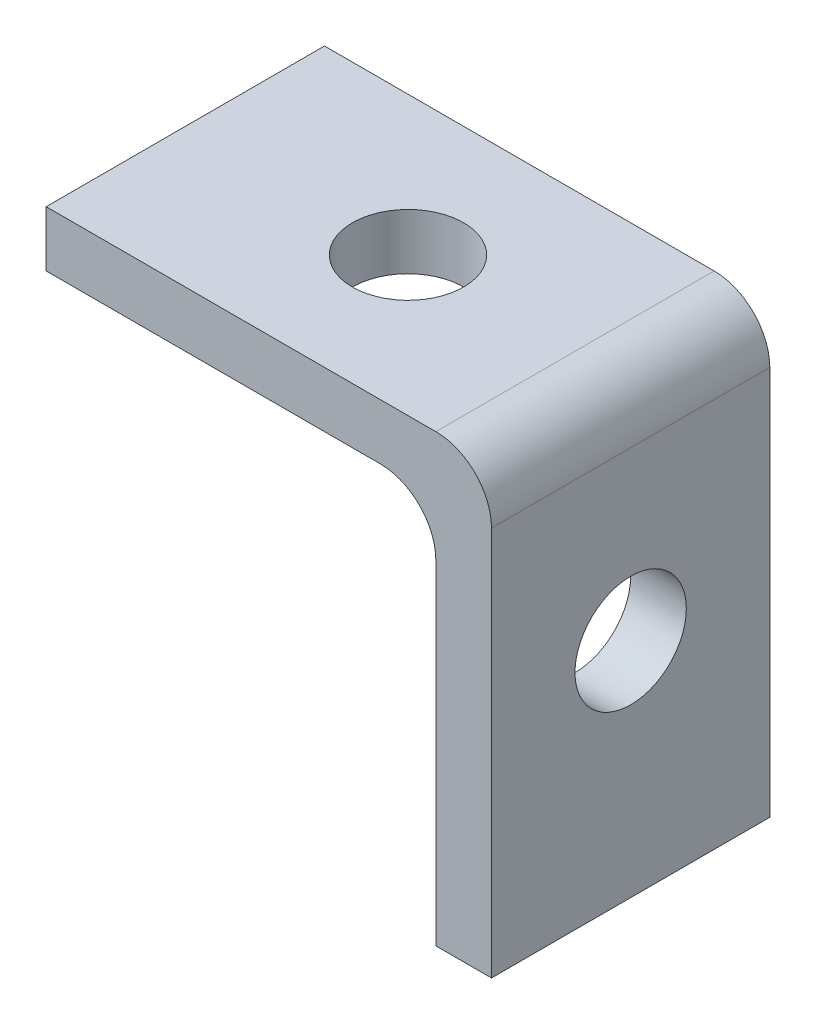
SolidWorks part; units mm, degrees
ref_plane "Plan de face" through (0, 0, 0) normal (0, 0, 1) x (1, 0, 0)
ref_plane "Plan de dessus" through (0, 0, 0) normal (0, 1, 0) x (1, 0, 0)
ref_plane "Plan de droite" through (0, 0, 0) normal (1, 0, 0) x (0, 0, -1)
sketch "Esquisse2" plane through (0, 0, 0) normal (0, 0, 1) x (1, 0, 0)
  line L0 (-1.2, 0) -> (-9.6, 0)
  line L1 (0, -1.2) -> (0, -9.6)
  line L2 (-9.6, 0) -> (-9.6, -1.2)
  line L3 (0, -9.6) -> (-1.2, -9.6)
  line L4 (-1.2, -9.6) -> (-1.2, -2.4)
  line L5 (-2.4, -1.2) -> (-9.6, -1.2)
  arc A0 (0, -1.2) -> (-1.2, 0) centre (-1.2, -1.2) ccw
  arc A1 (-1.2, -2.4) -> (-2.4, -1.2) centre (-2.4, -2.4) ccw
  point P9 (0, 0)
  dimension "D5" = 1.2
  dimension "D6" = 1.2
  dimension "D1" = 9.6
  dimension "D2" = 9.6
  dimension "D3" = 1.2
  dimension "D4" = 1.2
extrude "Boss.-Extru.2" add sketch "Esquisse2" along normal blind 6
sketch "Esquisse3" plane through (0, 0, 0) normal (0, 1, 0) x (1, 0, 0)
  line L0 (-9.7126, -3) -> (0, -3) construction
  line L1 (0, -6) -> (0, 0) construction
  line L2 (-9.6, -3) -> (-4.8, -3) construction
  line L3 (-9.6, -6) -> (-9.6, 0) construction
  circle A0 centre (-4.8, -3) radius 1.2
  dimension "D2" = 2.4
  dimension "D1" = 4.8
extrude "Enlèv. mat.-Extru.1" cut sketch "Esquisse3" against normal blind 6
sketch "Esquisse4" plane through (0, 0, 0) normal (1, 0, 0) x (0, 0, -1)
  line L0 (-3, -9.6) -> (-3, -4.8) construction
  line L1 (-6, -9.6) -> (0, -9.6) construction
  circle A0 centre (-3, -4.8) radius 1.2
  dimension "D2" = 2.4
  dimension "D1" = 4.8
extrude "Enlèv. mat.-Extru.2" cut sketch "Esquisse4" against normal blind 6
